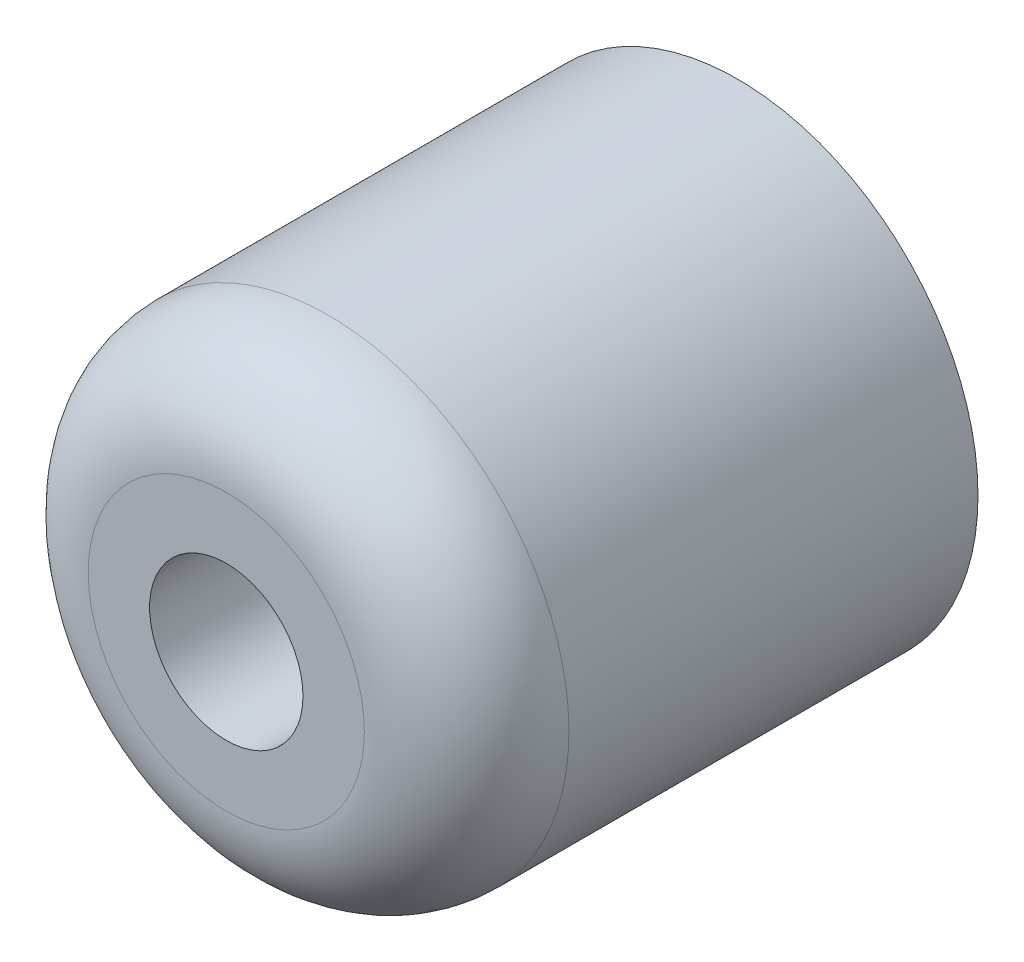
SolidWorks part; units mm, degrees
ref_plane "Спереди" through (0, 0, 0) normal (0, 0, 1) x (1, 0, 0)
ref_plane "Сверху" through (0, 0, 0) normal (0, 1, 0) x (1, 0, 0)
ref_plane "Справа" through (0, 0, 0) normal (1, 0, 0) x (0, 0, -1)
other "Configuration Table"
sketch "Эскиз2" plane through (0, 0, 0) normal (0, 0, 1) x (1, 0, 0)
  circle A0 centre (0, 0) radius 23.5
  dimension "D1" = 47
extrude "Бобышка-Вытянуть1" add sketch "Эскиз2" along normal blind 50
fillet "Скругление3" radius 10 1 edges at (23.5, 0, 50)
shell "Оболочка2" thickness 2
sketch "Эскиз5" plane through (0, 0, 48) normal (0, 0, -1) x (-1, 0, 0)
  circle A0 centre (0, 0) radius 9.5
  dimension "D1" = 19
extrude "Бобышка-Вытянуть2" add sketch "Эскиз5" along normal blind 48
sketch "Эскиз6" plane through (0, 0, 0) normal (0, 0, -1) x (-1, 0, 0)
  circle A0 centre (0, 0) radius 2.4
  dimension "D1" = 4.8
extrude "Вырез-Вытянуть1" cut sketch "Эскиз6" against normal through all
sketch "Эскиз7" plane through (0, 0, 0) normal (0, 0, -1) x (-1, 0, 0)
  line L0 (0, 29.4416) -> (0, -31.5446) construction
  line L1 (-0.6, 8.9376) -> (-0.6, 21.9376)
  line L2 (-0.6, 21.9376) -> (0.6, 21.9376)
  line L3 (0.6, 21.9376) -> (0.6, 8.9376)
  line L4 (0.6, 8.9376) -> (-0.6, 8.9376)
  line L5 (7.4402, 4.9884) -> (18.6985, 11.4884)
  line L6 (8.0402, 3.9492) -> (7.4402, 4.9884)
  line L7 (18.6985, 11.4884) -> (19.2985, 10.4492)
  line L8 (19.2985, 10.4492) -> (8.0402, 3.9492)
  line L9 (8.0402, -3.9492) -> (19.2985, -10.4492)
  line L10 (7.4402, -4.9884) -> (8.0402, -3.9492)
  line L11 (19.2985, -10.4492) -> (18.6985, -11.4884)
  line L12 (18.6985, -11.4884) -> (7.4402, -4.9884)
  line L13 (0.6, -8.9376) -> (0.6, -21.9376)
  line L14 (-0.6, -8.9376) -> (0.6, -8.9376)
  line L15 (0.6, -21.9376) -> (-0.6, -21.9376)
  line L16 (-0.6, -21.9376) -> (-0.6, -8.9376)
  line L17 (-7.4402, -4.9884) -> (-18.6985, -11.4884)
  line L18 (-8.0402, -3.9492) -> (-7.4402, -4.9884)
  line L19 (-18.6985, -11.4884) -> (-19.2985, -10.4492)
  line L20 (-19.2985, -10.4492) -> (-8.0402, -3.9492)
  line L21 (-8.0402, 3.9492) -> (-19.2985, 10.4492)
  line L22 (-7.4402, 4.9884) -> (-8.0402, 3.9492)
  line L23 (-19.2985, 10.4492) -> (-18.6985, 11.4884)
  line L24 (-18.6985, 11.4884) -> (-7.4402, 4.9884)
  circle A0 centre (0, 0) radius 23.5 construction
  point P32 (0, 0)
  dimension "D4" = 21.9376
  dimension "D1" = 1.2
  dimension "D2" = 0.6
  dimension "D3" = 13
  dimension "D5" = 6
extrude "Бобышка-Вытянуть3" add sketch "Эскиз7" against normal up to body
sketch "Эскиз8" plane through (0, 0, 50) normal (0, 0, 1) x (1, 0, 0)
  circle A0 centre (0, 0) radius 7.5
  dimension "D1" = 15
extrude "Вырез-Вытянуть2" cut sketch "Эскиз8" against normal blind 39
chamfer "Фаска1" distance 3 angle 45 1 edges at (2.4, 0, 11)
